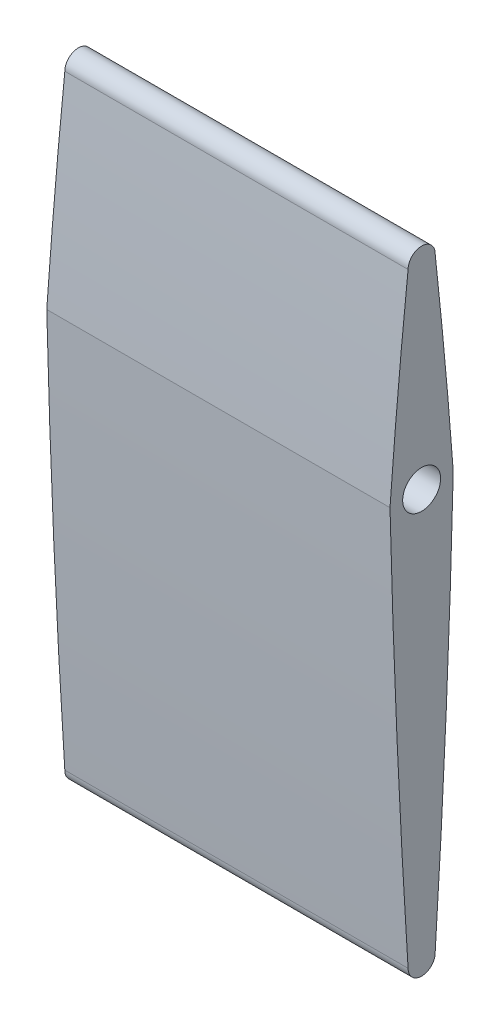
SolidWorks part; units mm, degrees
ref_plane "Front Plane" through (0, 0, 0) normal (1, 0, 0) x (0, 1, 0)
ref_plane "Top Plane" through (0, 0, 0) normal (0, 0, 1) x (0, 1, 0)
ref_plane "Right Plane" through (0, 0, 0) normal (0, 1, 0) x (-1, 0, 0)
sketch "Sketch1" plane through (0, 0, 0) normal (1, 0, 0) x (0, 1, 0)
  line L0 (0, 0) -> (-46.6667, 0) construction
  line L1 (0, 0) -> (23.3333, 0) construction
  circle A0 centre (0, 0) radius 3.5 construction
  arc A1 (-45.1667, 1.5) -> (-45.1667, -1.5) centre (-45.1667, 0) ccw
  arc A2 (21.8333, -1.5) -> (21.8333, 1.5) centre (21.8333, 0) ccw
  arc A3 (-45.1667, 1.5) -> (0, 3.5) centre (27.6309, -1131.504) cw
  arc A4 (-45.1667, -1.5) -> (0, -3.5) centre (27.6309, 1131.504) ccw
  arc A5 (0, 3.5) -> (21.8333, 1.5) centre (-48.6303, -647.5546) cw
  arc A6 (0, -3.5) -> (21.8333, -1.5) centre (-48.6303, 647.5546) ccw
  circle A7 centre (0, 0) radius 2.1
  dimension "D3" = 7
  dimension "D4" = 3
  dimension "D7" = 4.2
  dimension "D1" = 46.6667
  dimension "D2" = 23.3333
extrude "Boss-Extrude1" add sketch "Sketch1" along normal blind 38
